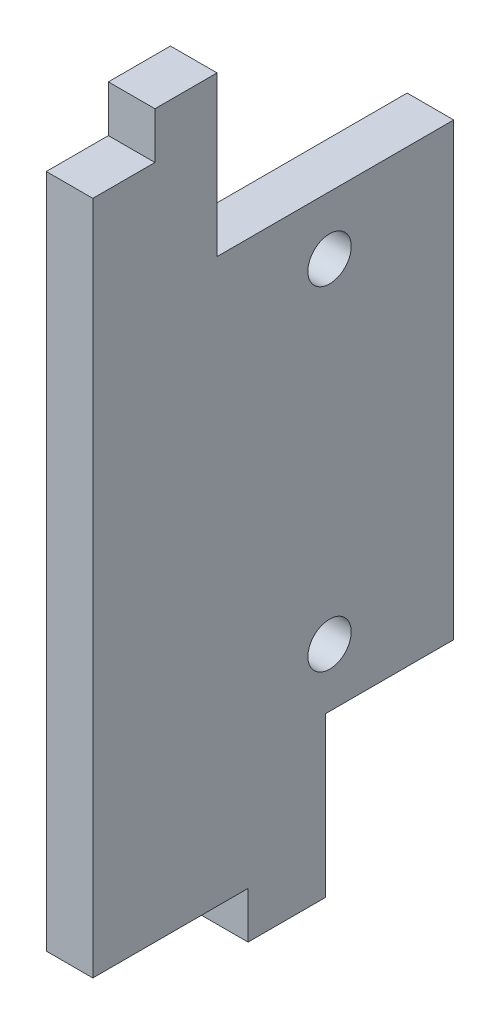
SolidWorks part; units mm, degrees
ref_plane "Front Plane" through (0, 0, 0) normal (0, 0, 1) x (1, 0, 0)
ref_plane "Top Plane" through (0, 0, 0) normal (0, 1, 0) x (1, 0, 0)
ref_plane "Right Plane" through (0, 0, 0) normal (1, 0, 0) x (0, 0, -1)
sketch "Sketch1" plane through (0, 0, 0) normal (1, 0, 0) x (0, 0, -1)
  line L0 (0, 24.75) -> (0, -24.75) construction
  line L1 (-7.5, -24.75) -> (7.5, -24.75)
  line L2 (-7.5, -24.75) -> (-7.5, 24.75)
  line L3 (-7.5, 24.75) -> (7.5, 24.75)
  line L4 (7.5, -24.75) -> (7.5, 24.75)
  dimension "D1" = 49.5
  dimension "D2" = 15
extrude "Boss-Extrude1" add sketch "Sketch1" along normal blind 3
sketch "Sketch2" plane through (0, 0, 0) normal (-1, 0, 0) x (0, 0, 1)
  line L0 (-7.5, -24.75) -> (-7.5, 24.75) construction
  line L5 (7.5, -24.75) -> (-2.5, -24.75)
  line L6 (7.5, -24.75) -> (7.5, -21.75)
  line L7 (7.5, -21.75) -> (-2.5, -21.75)
  line L8 (-2.5, -24.75) -> (-2.5, -21.75)
  line L10 (-7.5, 24.75) -> (-0.5, 24.75)
  line L11 (-7.5, 24.75) -> (-7.5, 14.5)
  line L12 (-7.5, 14.5) -> (-0.5, 14.5)
  line L13 (-0.5, 24.75) -> (-0.5, 14.5)
  line L14 (7.5, 24.75) -> (3.5, 24.75)
  line L15 (7.5, 24.75) -> (7.5, 21.75)
  line L16 (7.5, 21.75) -> (3.5, 21.75)
  line L17 (3.5, 24.75) -> (3.5, 21.75)
  point P4 (7.5, -24.75)
  dimension "D1" = 10.25
  dimension "D2" = 4
  dimension "D3" = 4
  dimension "D4" = 3
  dimension "D5" = 5
  dimension "D6" = 3
extrude "Cut-Extrude1" cut sketch "Sketch2" against normal through all
sketch "Sketch3" plane through (0, 0, -7.5) normal (0, 0, -1) x (-1, 0, 0)
  line L0 (0, -24.75) -> (0, 14.5) construction
  line L1 (-3, 14.5) -> (0, 14.5)
  line L2 (-3, 14.5) -> (-3, -14.5)
  line L3 (-3, -14.5) -> (0, -14.5)
  line L4 (0, 14.5) -> (0, -14.5)
  dimension "D1" = 29
extrude "Boss-Extrude2" add sketch "Sketch3" along normal blind 8.25
hole_wizard "#3 Clearance Hole1" positions "Sketch4" profile "Sketch5" hole size "#3" standard "ANSI Inch" end condition up to next
sketch "Sketch4" plane through (0, 0, 0) normal (-1, 0, 0) x (0, 0, 1)
  point P0 (-7.75, 10.75)
  point P2 (-7.75, -10.75)
  point P4 (-7.75, 10.75)
  point P6 (-7.75, -10.75)
sketch "Sketch5" plane through (0, 10.75, -7.75) normal (0, 1, 0) x (0, 0, 1)
  line L0 (0, 0) -> (0, 3)
  line L1 (0, 3) -> (1.397, 3)
  line L2 (1.397, 3) -> (1.397, 0)
  line L5 (1.397, 0) -> (0, 0)
  line L11 (0, -6.35) -> (0, 107.95) construction
  dimension "Thru Hole Dia." = 2.794
  dimension "Thru Hole Depth" = 3
